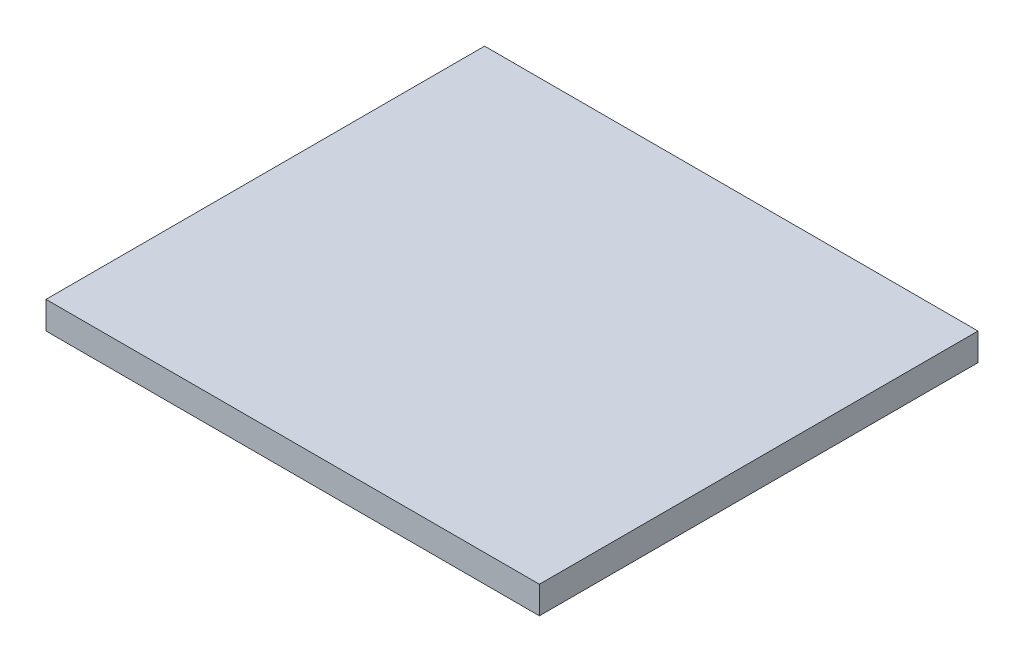
SolidWorks part; units mm, degrees
ref_plane "Plan de face" through (0, 0, 0) normal (0, 0, 1) x (1, 0, 0)
ref_plane "Plan de dessus" through (0, 0, 0) normal (0, 1, 0) x (1, 0, 0)
ref_plane "Plan de droite" through (0, 0, 0) normal (1, 0, 0) x (0, 0, -1)
sketch "Esquisse1" plane through (0, 0, 0) normal (0, 0, 1) x (1, 0, 0)
  line L1 (-45, 2.5) -> (45, 2.5)
  line L2 (-45, 2.5) -> (-45, -2.5)
  line L3 (-45, -2.5) -> (45, -2.5)
  line L4 (45, 2.5) -> (45, -2.5)
  line L5 (-45, 2.5) -> (45, -2.5) construction
  line L6 (-45, -2.5) -> (45, 2.5) construction
  point P0 (0, 0)
  dimension "D1" = 5
  dimension "D2" = 90
extrude "Boss.-Extru.1" add sketch "Esquisse1" along normal blind 80
